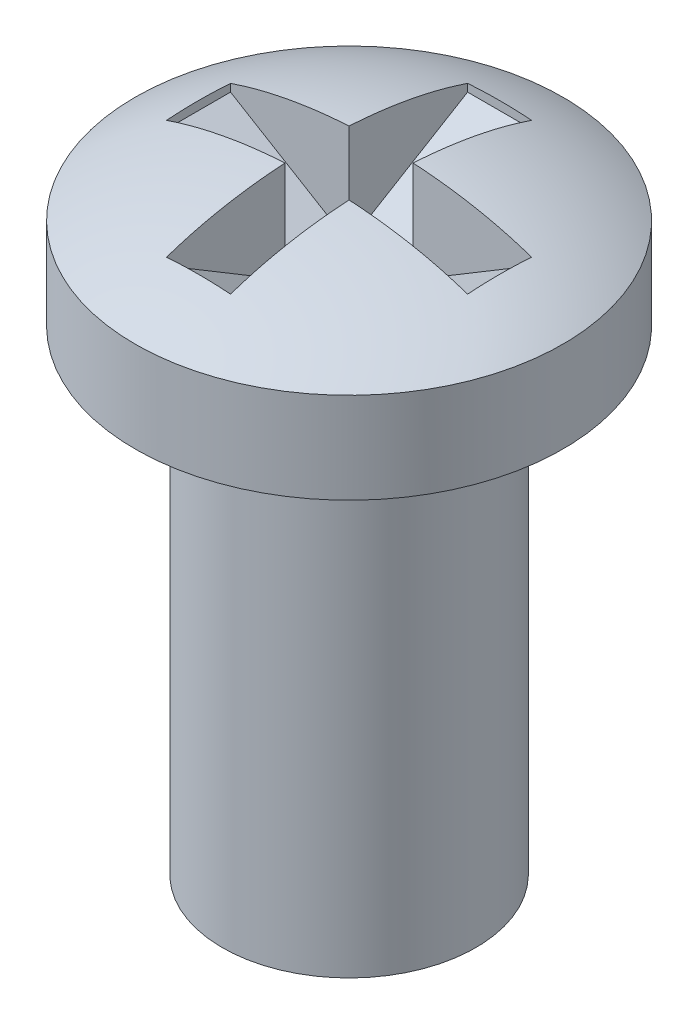
SolidWorks part; units mm, degrees
ref_plane "Front" through (0, 0, 0) normal (0, 0, 1) x (1, 0, 0)
ref_plane "Top" through (0, 0, 0) normal (0, 1, 0) x (1, 0, 0)
ref_plane "Right" through (0, 0, 0) normal (1, 0, 0) x (0, 0, -1)
sketch "草图2" plane through (0, 0, 0) normal (0, 0, 1) x (1, 0, 0)
  line L0 (0, 0) -> (0, -3.9) construction
  line L2 (1.35, -0.3265) -> (1.35, -0.9)
  line L3 (1.35, -0.9) -> (0.8, -0.9)
  line L4 (0.8, -0.9) -> (0.8, -3.9)
  line L5 (0.8, -3.9) -> (0, -3.9)
  line L6 (0, 0) -> (0, -3.9)
  spline S0 degree 3 poles (0, 0) (0.4632, 0) (0.9473, -0.0889) (1.35, -0.3265) knots 0 0 0 0 1 1 1 1
  point P8 (1.35, -0.2859)
  point P10 (0.7256, -0.1134)
  dimension "D1" = 1.35
  dimension "D3" = 0.8
  dimension "D4" = 3
revolve "旋转1" add sketch "草图2" angle 360 about L0
ref_plane "基准面2" through (0, 0, 0) normal (0, -1, 0) x (-1, 0, 0)
sketch "草图3" plane through (0, 0, 0) normal (0, -1, 0) x (-1, 0, 0)
  line L0 (-0.202, 0) -> (-0.202, 0.95)
  line L1 (-0.202, 0.95) -> (0.202, 0.95)
  line L3 (0.202, 0) -> (-0.202, 0)
  line L4 (0, 1.3421) -> (0, 0) construction
  line L5 (0.202, 0) -> (0.202, 0.95)
  dimension "D1" = 0.95
extrude "切除-拉伸1" cut sketch "草图3" along normal blind 0.2
pattern_circular "阵列(圆周)4" count 4 over 360 about axis through (0, 0, 0) along (0, 1, 0) of "切除-拉伸1"
sketch "草图6" plane through (0, 0, 0.202) normal (0, 0, -1) x (-1, 0, 0)
  line L0 (0.95, -0.2) -> (0, -0.7708)
  line L1 (0, -0.7708) -> (-0.95, -0.2)
  line L2 (-0.95, -0.2) -> (0.95, -0.2)
  line L3 (0, 0) -> (0, -0.7708) construction
  point P6 (0, 0.3708)
  point P8 (0, -0.9)
  point P9 (0, -0.7522)
  point P11 (0, 0)
  dimension "D1" = 118
extrude "切除-拉伸4" cut sketch "草图6" along normal up to surface (0.404 mm away) up to face at (-0.4825, -0.1234, -0.202)
sketch "草图7" plane through (0.202, 0, 0) normal (-1, 0, 0) x (0, 0, 1)
  line L7 (0.95, -0.2) -> (0, -0.7708)
  line L8 (-0.202, -0.7708) -> (0.202, -0.7708) construction
  line L9 (0, -0.7708) -> (-0.95, -0.2)
  line L10 (-0.95, -0.2) -> (-0.202, -0.2) construction
  line L11 (-0.95, -0.2) -> (0.95, -0.2)
extrude "切除-拉伸5" cut sketch "草图7" along normal up to surface (0.404 mm away) up to face at (-0.202, -0.131, -0.5551)
ref_plane "基准面1" through (0, -0.6494, 0) normal (0, -1, 0) x (-1, 0, 0)
sketch "草图8" plane through (0, -0.6494, 0) normal (0, -1, 0) x (-1, 0, 0)
  line L0 (0.202, 0.202) -> (0.95, 0.202) construction
  line L1 (0.202, 0.202) -> (-0.202, 0.202)
  line L2 (0.202, 0.202) -> (0.202, -0.202)
  line L3 (0.202, -0.202) -> (-0.202, -0.202)
  line L4 (-0.202, 0.202) -> (-0.202, -0.202)
  line L5 (-0.202, 0.202) -> (-0.202, -0.202) construction
extrude "凸台-拉伸1" add sketch "草图8" along normal blind 0.3
